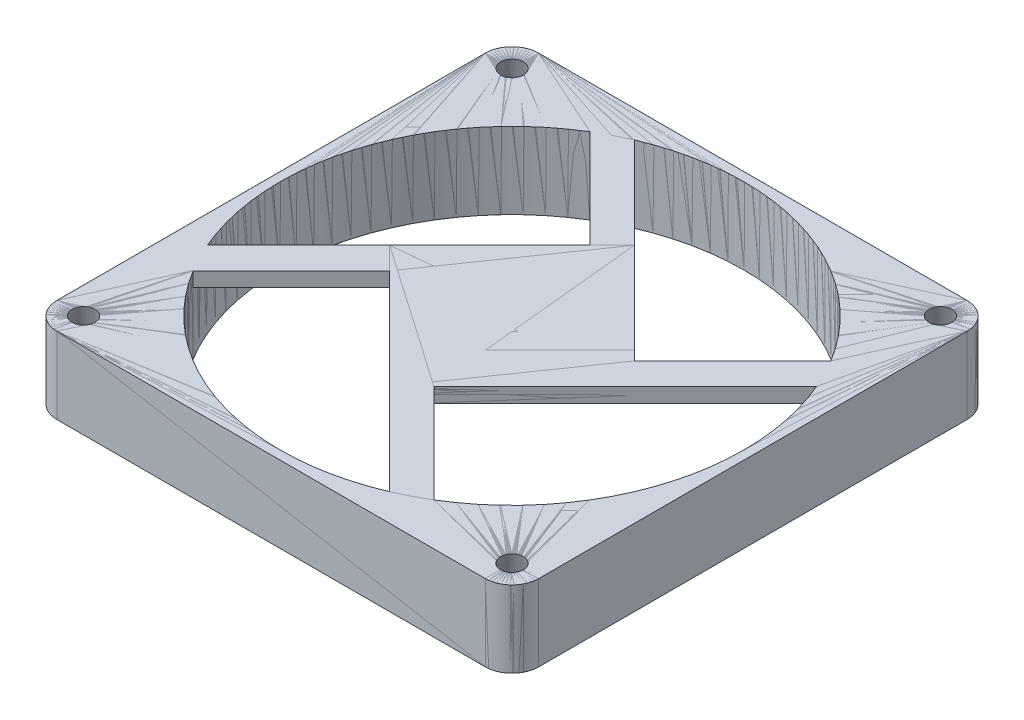
SolidWorks part; units mm, degrees
ref_plane "Front Plane" through (0, 0, 0) normal (0, 0, 1) x (1, 0, 0)
ref_plane "Top Plane" through (0, 0, 0) normal (0, 1, 0) x (1, 0, 0)
ref_plane "Right Plane" through (0, 0, 0) normal (1, 0, 0) x (0, 0, -1)
sketch "Sketch1" plane through (0, 0, 0) normal (0, 1, 0) x (1, 0, 0)
  line L1 (-46, -45.974) -> (46, -45.974)
  line L2 (-46, -45.974) -> (-46, 45.974)
  line L3 (-46, 45.974) -> (46, 45.974)
  line L4 (46, -45.974) -> (46, 45.974)
  line L5 (-46, -45.974) -> (46, 45.974) construction
  line L6 (-46, 45.974) -> (46, -45.974) construction
  point P0 (0, 0)
  dimension "D1" = 91.948
  dimension "D2" = 92
extrude "Boss-Extrude1" add sketch "Sketch1" along normal blind 14.605
sketch "Sketch2" plane through (0, 14.605, 0) normal (0, 1, 0) x (1, 0, 0)
  circle A0 centre (0, 0) radius 44.323
extrude "Cut-Extrude1" cut sketch "Sketch2" against normal blind 14.605
sketch "Sketch3" plane through (0, 14.605, 0) normal (0, 1, 0) x (1, 0, 0)
  line L0 (46, 45.974) -> (-46, 45.974) construction
  line L1 (-46, 45.974) -> (-46, -45.974) construction
  line L2 (-46, -45.974) -> (46, -45.974) construction
  line L3 (46, -45.974) -> (46, 45.974) construction
  circle A0 centre (-40.92, 40.894) radius 2.1844
  circle A1 centre (40.92, 40.894) radius 2.1844
  circle A2 centre (40.92, -40.894) radius 2.1844
  circle A3 centre (-40.92, -40.894) radius 2.1844
  point P16 (0, 0)
  point P18 (51.3325, 40.8094)
  dimension "D1" = 4.3688
  dimension "D2" = 4.3688
  dimension "D3" = 4.3688
  dimension "D4" = 4.3688
  dimension "D5" = 5.08
  dimension "D6" = 5.08
  dimension "D7" = 5.08
  dimension "D8" = 5.08
  dimension "D9" = 5.08
  dimension "D10" = 5.08
  dimension "D11" = 5.08
  dimension "D12" = 5.08
fillet "Fillet1" radius 5.08 4 edges at (-46, 7.3025, -45.974) (46, 7.3025, -45.974) (46, 7.3025, 45.974) (-46, 7.3025, 45.974)
extrude "Cut-Extrude2" cut sketch "Sketch3" against normal blind 14.605 contours A2 | A3 | A1 | A0
sketch "Sketch4" plane through (0, 14.605, 0) normal (0, 1, 0) x (1, 0, 0)
  line L0 (-26.8461, 41.7533) -> (5.8718, 9.0355)
  line L1 (-26.8461, 41.7533) -> (-22.6253, 45.974)
  line L2 (5.8718, 9.0355) -> (10.0925, 13.2562)
  line L3 (-22.6253, 45.974) -> (10.0925, 13.2562)
  line L4 (40.92, 45.974) -> (-40.92, 45.974) construction
  line L6 (-23.3487, 0) -> (0, -23.3487)
  line L7 (-23.3487, 0) -> (0, 23.3487)
  line L8 (0, -23.3487) -> (23.3487, 0)
  line L9 (0, 23.3487) -> (23.3487, 0)
  line L11 (0, 23.3487) -> (0, -23.3487)
  circle A0 centre (0, 0) radius 44.323 construction
  point P0 (0, 0)
  point P7 (0, -23.3487)
  point P8 (-99.1261, 47.6915)
  point P11 (-1.7101, 38.0501)
  point P15 (-23.3487, 0)
  point P17 (23.3487, 0)
  point P18 (-23.3487, 0)
  point P19 (23.3487, 0)
  point P20 (0, 0)
  dimension "D1" = 5.969
  dimension "D2" = 45
  dimension "D3" = 0
  dimension "D4" = 33.02
  dimension "D5" = 33.02
  dimension "D7" = 0
  dimension "D8" = 0
extrude "Boss-Extrude2" add sketch "Sketch4" against normal blind 2.794 contours L0 L11 L8 L9 L2 | L11 L0 L7 L6
pattern_circular "CirPattern2" count 4 over 360 about axis through (0, 0, 0) along (0, 1, 0) of bodies 104
